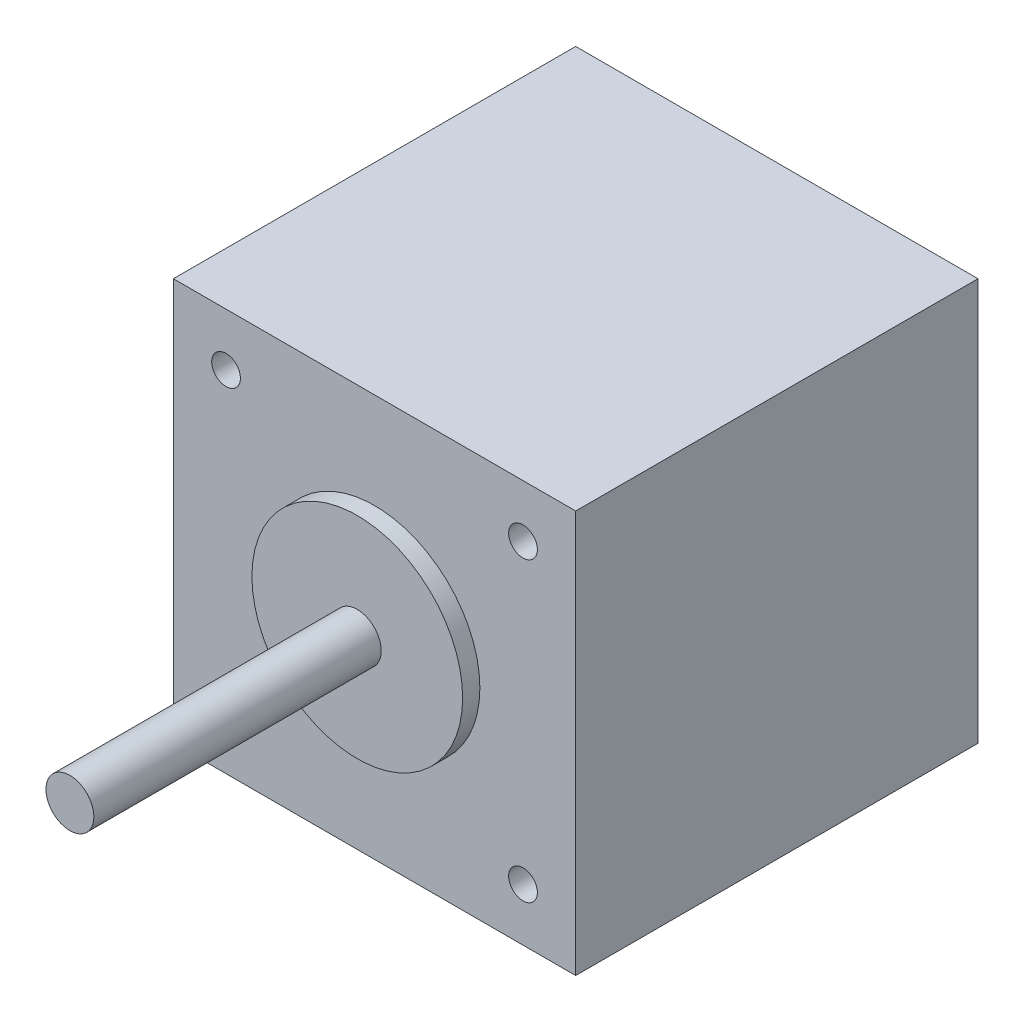
SolidWorks part; units mm, degrees
ref_plane "前视基准面" through (0, 0, 0) normal (0, 0, 1) x (1, 0, 0)
ref_plane "上视基准面" through (0, 0, 0) normal (0, 1, 0) x (1, 0, 0)
ref_plane "右视基准面" through (0, 0, 0) normal (1, 0, 0) x (0, 0, -1)
sketch "草图1" plane through (0, 0, 0) normal (0, 0, 1) x (1, 0, 0)
  line L1 (21, -21) -> (-21, -21)
  line L2 (21, -21) -> (21, 21)
  line L3 (21, 21) -> (-21, 21)
  line L4 (-21, -21) -> (-21, 21)
  line L5 (21, -21) -> (-21, 21) construction
  line L6 (21, 21) -> (-21, -21) construction
  point P0 (0, 0)
  dimension "D1" = 42
  dimension "D2" = 42
extrude "凸台-拉伸1" add sketch "草图1" along normal blind 42
sketch "草图2" plane through (0, 0, 42) normal (0, 0, 1) x (1, 0, 0)
  line L0 (0, 11.251) -> (0, 0) construction
  line L1 (0, 0) -> (8.81, 0) construction
  circle A0 centre (15.5, 15.5) radius 1.5
  circle A1 centre (-15.5, 15.5) radius 1.5
  circle A2 centre (-15.5, -15.5) radius 1.5
  circle A3 centre (15.5, -15.5) radius 1.5
  dimension "D1" = 31
  dimension "D3" = 3
  dimension "D2" = 31
extrude "切除-拉伸1" cut sketch "草图2" against normal blind 10
sketch "草图3" plane through (0, 0, 42) normal (0, 0, 1) x (1, 0, 0)
  circle A0 centre (0, 0) radius 11
  dimension "D1" = 22
extrude "凸台-拉伸2" add sketch "草图3" along normal blind 1.8
sketch "草图4" plane through (0, 0, 43.8) normal (0, 0, 1) x (1, 0, 0)
  circle A0 centre (0, 0) radius 2.5
  dimension "D1" = 5
extrude "凸台-拉伸3" add sketch "草图4" along normal blind 30
